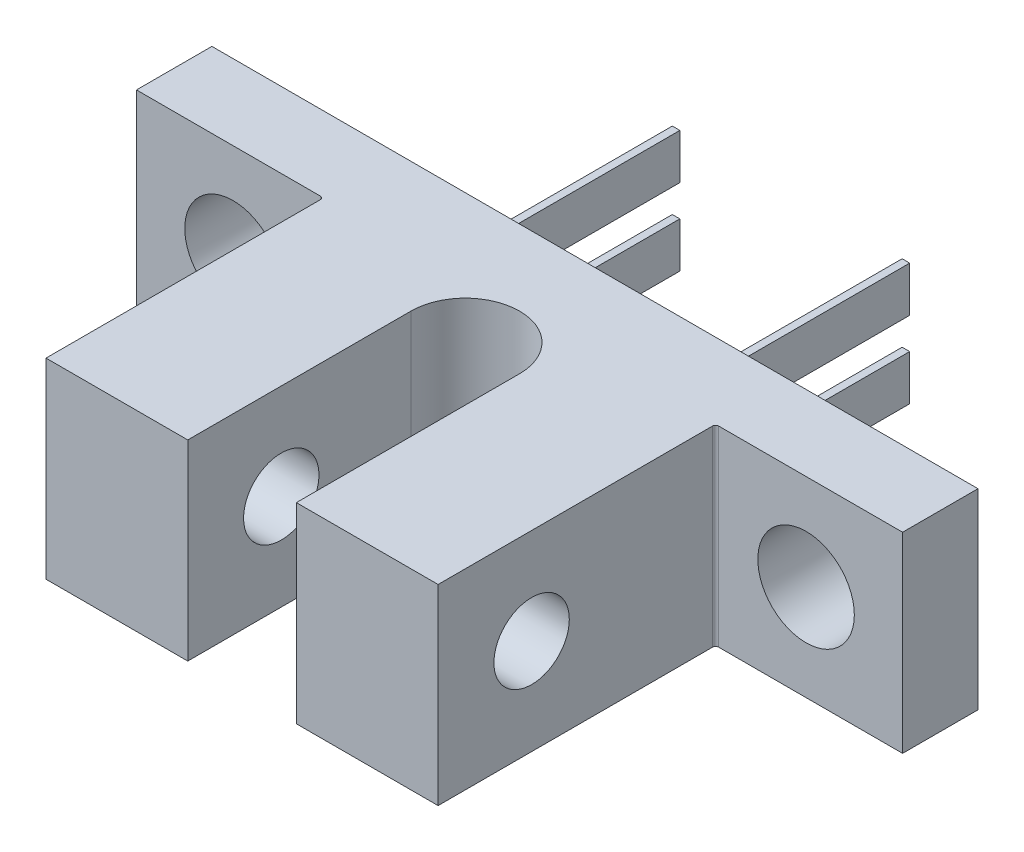
SolidWorks part; units mm, degrees
ref_plane "Front Plane" through (0, 0, 0) normal (0, 0, 1) x (1, 0, 0)
ref_plane "Top Plane" through (0, 0, 0) normal (0, 1, 0) x (1, 0, 0)
ref_plane "Right Plane" through (0, 0, 0) normal (1, 0, 0) x (0, 0, -1)
ref_plane "Plane1" through (0, -1.0891, 0) normal (0, -1, 0) x (1, 0, 0)
sketch "Sketch1" plane through (0, -1.0891, 0) normal (0, -1, 0) x (1, 0, 0)
  line L0 (-10.9265, 0) -> (14.4735, 0)
  line L1 (14.4735, 0) -> (14.4735, 11.7)
  line L2 (14.4735, 11.7) -> (-10.9265, 11.7)
  line L3 (-10.9265, 11.7) -> (-10.9265, 0)
extrude "Boss-Extrude1" add sketch "Sketch1" against normal blind 6.35
sketch "Sketch2" plane through (0, 5.2609, 0) normal (0, 1, 0) x (-1, 0, 0)
  line L0 (-8.2735, 2.5) -> (-8.2735, 11.7)
  line L1 (-8.2735, 11.7) -> (-14.4735, 11.7)
  line L2 (-14.4735, 11.7) -> (-14.4735, 2.5)
  line L3 (-14.4735, 2.5) -> (-8.2735, 2.5)
extrude "Cut-Extrude1" cut sketch "Sketch2" against normal through all
sketch "Sketch3" plane through (0, 5.2609, 0) normal (0, 1, 0) x (-1, 0, 0)
  line L0 (-3.5735, 11.7) -> (-3.5735, 4.3)
  line L1 (0.0265, 4.3) -> (0.0265, 11.7)
  line L2 (0.0265, 11.7) -> (-3.5735, 11.7)
  arc A0 (-3.5735, 4.3) -> (0.0265, 4.3) centre (-1.7735, 4.3) ccw
extrude "Cut-Extrude2" cut sketch "Sketch3" against normal through all
sketch "Sketch4" plane through (0, 5.2609, 0) normal (0, 1, 0) x (-1, 0, 0)
  line L0 (4.7265, 11.7) -> (4.7265, 2.5)
  line L1 (4.7265, 2.5) -> (10.9265, 2.5)
  line L2 (10.9265, 2.5) -> (10.9265, 11.7)
  line L3 (10.9265, 11.7) -> (4.7265, 11.7)
extrude "Cut-Extrude3" cut sketch "Sketch4" against normal through all
sketch "Sketch5" plane through (0, 0, 0) normal (0, 0, -1) x (-1, 0, 0)
  line L0 (1.9115, 0.0659) -> (1.9115, 1.5659)
  line L1 (1.9115, 1.5659) -> (2.1615, 1.5659)
  line L2 (2.1615, 1.5659) -> (2.1615, 0.0659)
  line L3 (2.1615, 0.0659) -> (1.9115, 0.0659)
extrude "Boss-Extrude2" add sketch "Sketch5" along normal blind 6.5
sketch "Sketch6" plane through (0, 0, 0) normal (0, 0, -1) x (-1, 0, 0)
  line L0 (2.1615, 2.6059) -> (1.9115, 2.6059)
  line L1 (1.9115, 2.6059) -> (1.9115, 4.1059)
  line L2 (1.9115, 4.1059) -> (2.1615, 4.1059)
  line L3 (2.1615, 4.1059) -> (2.1615, 2.6059)
extrude "Boss-Extrude3" add sketch "Sketch6" along normal blind 6.5
sketch "Sketch7" plane through (0, 0, 0) normal (0, 0, -1) x (-1, 0, 0)
  line L0 (-5.4585, 4.1059) -> (-5.4585, 2.6059)
  line L1 (-5.4585, 2.6059) -> (-5.7085, 2.6059)
  line L2 (-5.7085, 2.6059) -> (-5.7085, 4.1059)
  line L3 (-5.7085, 4.1059) -> (-5.4585, 4.1059)
extrude "Boss-Extrude4" add sketch "Sketch7" along normal blind 6.5
sketch "Sketch8" plane through (0, 0, 0) normal (0, 0, -1) x (-1, 0, 0)
  line L0 (-5.7085, 1.5659) -> (-5.4585, 1.5659)
  line L1 (-5.4585, 1.5659) -> (-5.4585, 0.0659)
  line L2 (-5.4585, 0.0659) -> (-5.7085, 0.0659)
  line L3 (-5.7085, 0.0659) -> (-5.7085, 1.5659)
extrude "Boss-Extrude5" add sketch "Sketch8" along normal blind 6.5
hole_wizard "Hole1" positions "Sketch10" profile "Sketch9" legacy
sketch "Sketch10" plane through (0, 0, 2.5) normal (0, 0, 1) x (1, 0, 0)
  point P0 (11.2735, 2.0859)
sketch "Sketch9" plane through (11.2735, 2.0859, 2.5) normal (1, 0, 0) x (0, -1, 0)
  line L0 (0, 0) -> (0, 9)
  line L1 (0, 9) -> (1.6, 9)
  line L2 (1.6, 9) -> (1.6, 0)
  line L3 (1.6, 0) -> (0, 0)
  line L4 (0, 110) -> (0, -10) construction
  dimension "Diameter" = 3.2
  dimension "Depth" = 9
hole_wizard "Hole2" positions "Sketch12" profile "Sketch11" legacy
sketch "Sketch12" plane through (0, 0, 2.5) normal (0, 0, 1) x (1, 0, 0)
  point P0 (-7.7265, 2.0859)
sketch "Sketch11" plane through (-7.7265, 2.0859, 2.5) normal (1, 0, 0) x (0, -1, 0)
  line L0 (0, 0) -> (0, 9)
  line L1 (0, 9) -> (1.6, 9)
  line L2 (1.6, 9) -> (1.6, 0)
  line L3 (1.6, 0) -> (0, 0)
  line L4 (0, 110) -> (0, -10) construction
  dimension "Diameter" = 3.2
  dimension "Depth" = 9
hole_wizard "Hole3" positions "Sketch14" profile "Sketch13" legacy
sketch "Sketch14" plane through (-4.7265, 0, 0) normal (-1, 0, 0) x (0, 0, 1)
  point P0 (8.6, 2.0859)
sketch "Sketch13" plane through (-4.7265, 2.0859, 8.6) normal (0, 1, 0) x (0, 0, 1)
  line L0 (0, 0) -> (0, 4.7)
  line L1 (0, 4.7) -> (1.25, 4.7)
  line L2 (1.25, 4.7) -> (1.25, 0)
  line L3 (1.25, 0) -> (0, 0)
  line L4 (0, 110) -> (0, -10) construction
  dimension "Diameter" = 2.5
  dimension "Depth" = 4.7
hole_wizard "Hole4" positions "Sketch16" profile "Sketch15" legacy
sketch "Sketch16" plane through (8.2735, 0, 0) normal (1, 0, 0) x (0, 0, -1)
  point P0 (-8.6, 2.0859)
sketch "Sketch15" plane through (8.2735, 2.0859, 8.6) normal (0, 1, 0) x (0, 0, -1)
  line L0 (0, 0) -> (0, 19.2)
  line L1 (0, 19.2) -> (1.25, 19.2)
  line L2 (1.25, 19.2) -> (1.25, 0)
  line L3 (1.25, 0) -> (0, 0)
  line L4 (0, 110) -> (0, -10) construction
  dimension "Diameter" = 2.5
  dimension "Depth" = 19.2
fillet "Fillet1" radius 0.1 1 edges at (-4.7265, 2.0859, 2.5)
fillet "Fillet2" radius 0.1 1 edges at (8.2735, 2.0859, 2.5)
